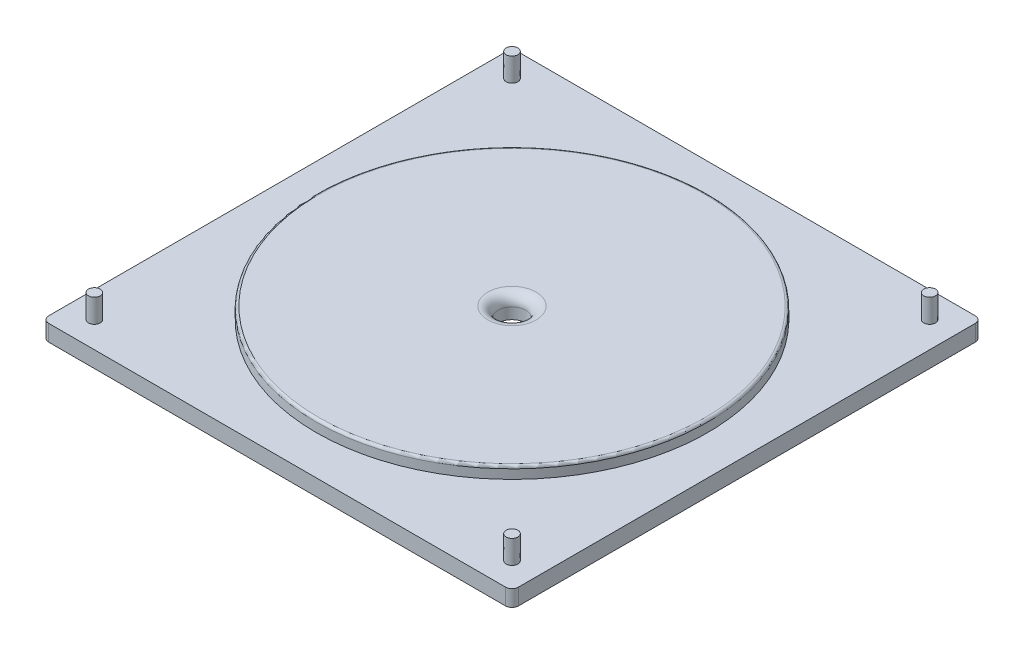
SolidWorks part; units mm, degrees
ref_plane "Front Plane" through (0, 0, 0) normal (0, 0, 1) x (1, 0, 0)
ref_plane "Top Plane" through (0, 0, 0) normal (0, 1, 0) x (1, 0, 0)
ref_plane "Right Plane" through (0, 0, 0) normal (1, 0, 0) x (0, 0, -1)
sketch "Sketch1" plane through (0, 0, 0) normal (0, 1, 0) x (1, 0, 0)
  line L1 (-0.6547, 42.9921) -> (90.7853, 42.9921)
  line L2 (-0.6547, 42.9921) -> (-0.6547, -48.4479)
  line L3 (-0.6547, -48.4479) -> (90.7853, -48.4479)
  line L4 (90.7853, 42.9921) -> (90.7853, -48.4479)
  dimension "D1" = 91.44
  dimension "D2" = 91.44
extrude "Boss-Extrude1" add sketch "Sketch1" along normal blind 3.175
sketch "Sketch2" plane through (0, 3.175, 0) normal (0, 1, 0) x (1, 0, 0)
  circle A0 centre (45.0653, -2.7279) radius 38.1
  dimension "D1" = 76.2
extrude "Boss-Extrude2" add sketch "Sketch2" along normal blind 2.286
sketch "Sketch3" plane through (0, 3.175, 0) normal (0, 1, 0) x (1, 0, 0)
  line L1 (90.7853, -48.4479) -> (90.7853, 42.9921) construction
  line L2 (-0.6547, -48.4479) -> (90.7853, -48.4479) construction
  line L3 (45.0653, -48.4479) -> (45.0653, 42.9921) construction
  line L4 (90.7853, 42.9921) -> (-0.6547, 42.9921) construction
  line L5 (-0.6547, -2.7279) -> (90.7853, -2.7279) construction
  line L6 (-0.6547, 42.9921) -> (-0.6547, -48.4479) construction
  line L7 (-0.6547, -43.3679) -> (4.4253, -43.3679) construction
  line L8 (90.7853, 37.9121) -> (85.7053, 37.9121) construction
  line L9 (-0.6547, 37.9121) -> (4.4253, 37.9121) construction
  circle A0 centre (4.4253, 37.9121) radius 1.143
  circle A1 centre (4.4253, -43.3679) radius 1.143
  circle A2 centre (85.7053, -43.3679) radius 1.143
  circle A3 centre (85.7053, 37.9121) radius 1.143
  dimension "D3" = 2.286
  dimension "D4" = 2.286
extrude "Boss-Extrude3" add sketch "Sketch3" along normal blind 4.572
sketch "Sketch4" plane through (0, 5.461, 0) normal (0, 1, 0) x (1, 0, 0)
  line L0 (45.0653, -40.8279) -> (45.0653, 35.3721) construction
  circle A0 centre (45.0653, -2.7279) radius 38.1 construction
  circle A1 centre (45.0653, -2.7279) radius 38.1 construction
  circle A2 centre (45.0653, -2.7279) radius 2.667
  dimension "D1" = 5.334
extrude "Cut-Extrude1" cut sketch "Sketch4" against normal through all
fillet "Fillet1" radius 2.032 1 edges at (45.0653, 5.461, 5.3949)
fillet "Fillet3" radius 1.27 4 edges at (-0.6547, 1.5875, -42.9921) (90.7853, 1.5875, -42.9921) (90.7853, 1.5875, 48.4479) (-0.6547, 1.5875, 48.4479)
sketch "Sketch5" plane through (0, 0, 0) normal (0, -1, 0) x (1, 0, 0)
  circle A0 centre (45.0653, 2.7279) radius 20.32
  dimension "D1" = 40.64
extrude "Cut-Extrude2" cut sketch "Sketch5" against normal blind 1.27
fillet "Fillet4" radius 0.762 1 edges at (45.0653, 0, -17.5921)
fillet "Fillet6" radius 0.508 1 edges at (45.0653, 5.461, 40.8279)
